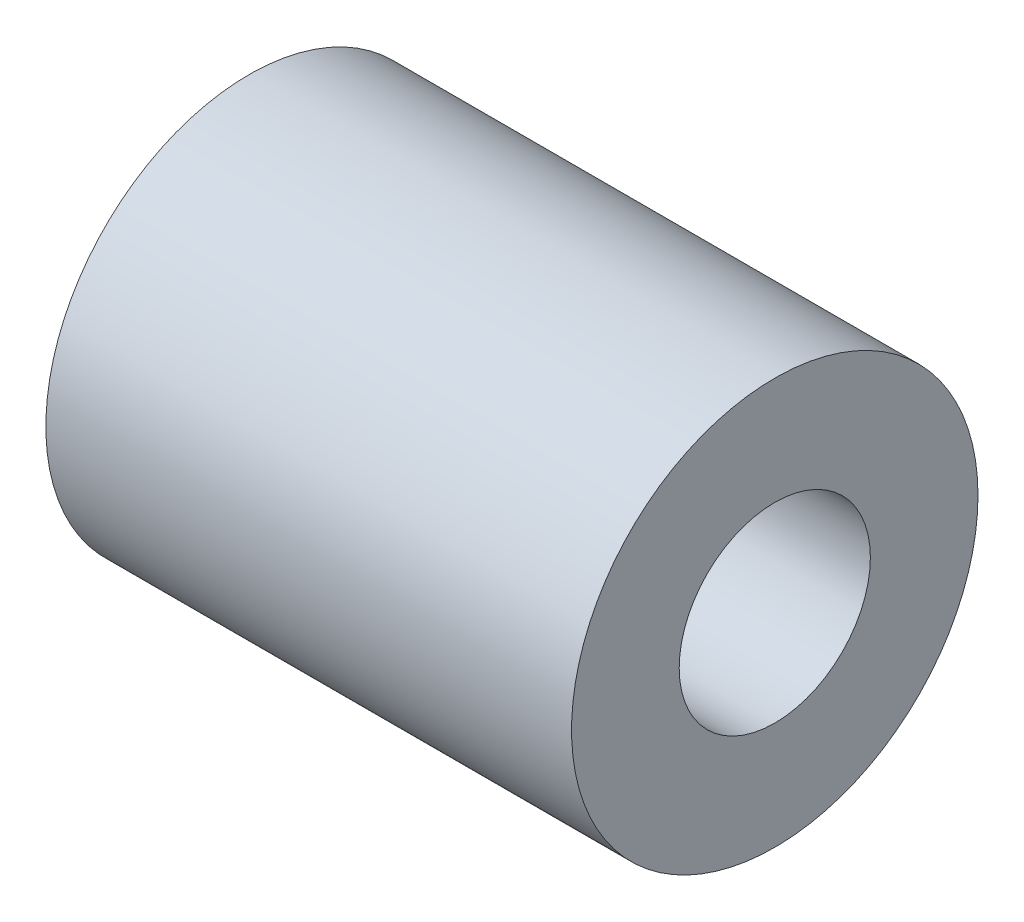
SolidWorks part; units mm, degrees
ref_plane "Plano frontal" through (0, 0, 0) normal (0, 0, 1) x (1, 0, 0)
ref_plane "Plano superior" through (0, 0, 0) normal (0, 1, 0) x (1, 0, 0)
ref_plane "Plano direito" through (0, 0, 0) normal (1, 0, 0) x (0, 0, -1)
sketch "Esboço1" plane through (0, 0, 0) normal (0, 0, 1) x (1, 0, 0)
  line L0 (17.4625, 13.5001) -> (-17.4625, 13.5001)
  line L1 (-17.4625, 13.5001) -> (-17.4625, 6.35)
  line L2 (-17.4625, 6.35) -> (17.4625, 6.35)
  line L3 (17.4625, 6.35) -> (17.4625, 13.5001)
  line L4 (-17.4625, 0) -> (17.4625, 0) construction
revolve "Revolução1" add sketch "Esboço1" angle 360 about L4
